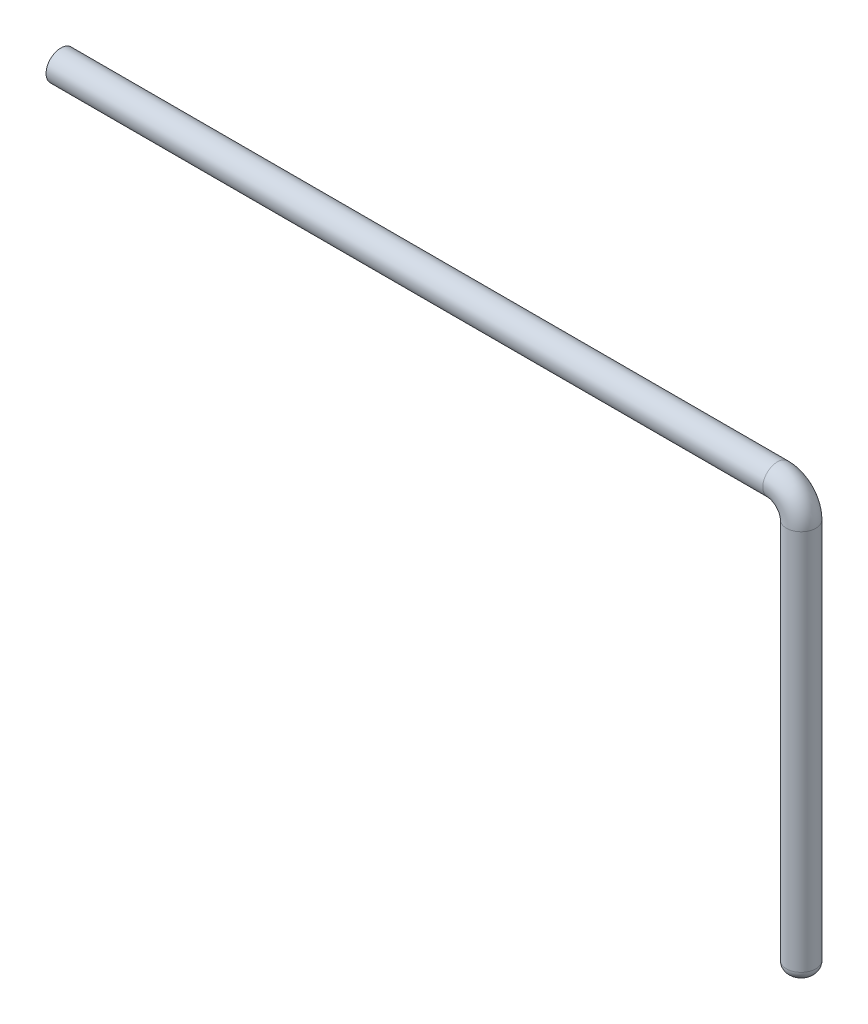
SolidWorks part; units mm, degrees
ref_plane "前视基准面" through (0, 0, 0) normal (0, 0, 1) x (1, 0, 0)
ref_plane "上视基准面" through (0, 0, 0) normal (0, 1, 0) x (1, 0, 0)
ref_plane "右视基准面" through (0, 0, 0) normal (1, 0, 0) x (0, 0, -1)
sketch "草图1" plane through (0, 0, 0) normal (0, 0, 1) x (1, 0, 0)
  line L0 (36.7076, 26.8114) -> (51.8276, 26.8114)
  line L1 (52.3276, 26.3114) -> (52.3276, 18.0614)
  arc A0 (52.3276, 26.3114) -> (51.8276, 26.8114) centre (51.8276, 26.3114) ccw
  dimension "D1" = 0.5
sweep "扫描1" add path "草图1" circular profile diameter 0.62 parameters "D3"=0.62
fillet "圆角1" radius 0.2 1 edges at (52.3276, 18.0614, 0.31)
